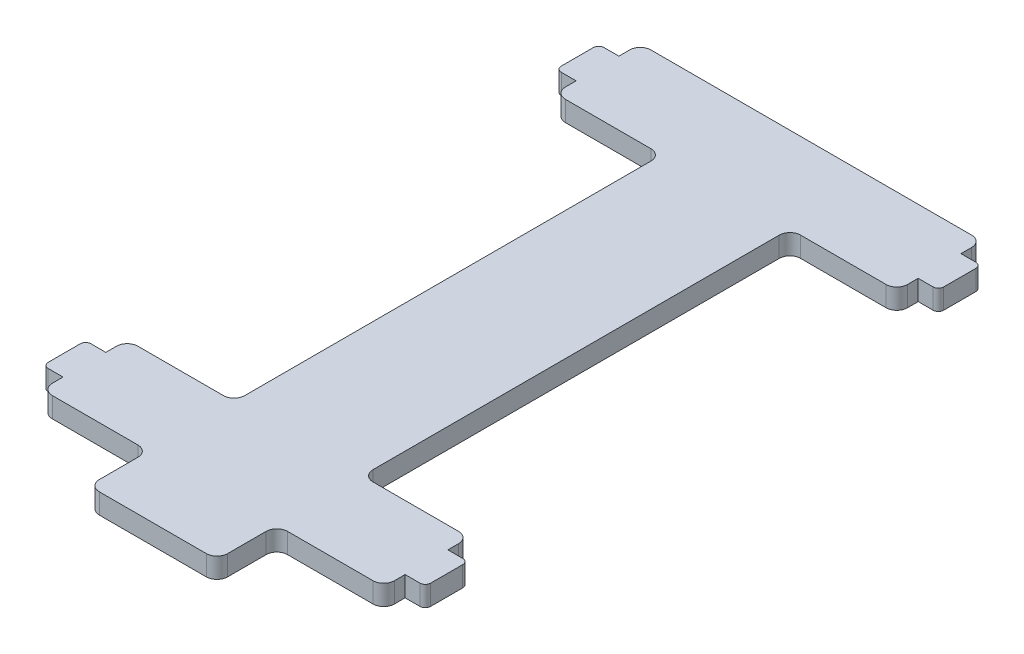
SolidWorks part; units mm, degrees
ref_plane "Front Plane" through (0, 0, 0) normal (0, 0, 1) x (1, 0, 0)
ref_plane "Top Plane" through (0, 0, 0) normal (0, 1, 0) x (1, 0, 0)
ref_plane "Right Plane" through (0, 0, 0) normal (1, 0, 0) x (0, 0, -1)
sketch "Sketch1" plane through (0, 0, 0) normal (0, 1, 0) x (1, 0, 0)
  line L0 (25.4, 31.75) -> (9.525, 31.75)
  line L1 (-25.4, -44.45) -> (-9.525, -44.45)
  line L2 (-25.4, -44.45) -> (-25.4, -31.75)
  line L4 (25.4, -44.45) -> (25.4, -31.75)
  line L5 (-25.4, -44.45) -> (25.4, 44.45) construction
  line L6 (-25.4, 44.45) -> (25.4, -44.45) construction
  line L7 (9.525, 31.75) -> (9.525, -31.75)
  line L8 (9.525, -31.75) -> (25.4, -31.75)
  line L9 (-25.4, -31.75) -> (-9.525, -31.75)
  line L10 (-9.525, -31.75) -> (-9.525, 31.75)
  line L11 (-9.525, 31.75) -> (-25.4, 31.75)
  line L12 (0, -44.45) -> (0, 44.45) construction
  line L13 (-25.4, -31.75) -> (-25.4, 31.75) construction
  line L14 (-25.4, 31.75) -> (-25.4, 44.45)
  line L15 (25.4, -31.75) -> (25.4, 31.75) construction
  line L16 (25.4, 31.75) -> (25.4, 44.45)
  line L20 (0, -44.45) -> (9.525, -44.45) construction
  line L21 (9.525, -44.45) -> (25.4, -44.45)
  line L22 (-9.525, -44.45) -> (0, -44.45) construction
  line L26 (-9.525, 44.45) -> (0, 44.45) construction
  line L27 (-25.4, 44.45) -> (25.4, 44.45)
  line L28 (0, 44.45) -> (-25.4, 44.45) construction
  line L29 (-9.525, -44.45) -> (-9.525, -53.34)
  line L30 (-9.525, -53.34) -> (9.525, -53.34)
  line L31 (9.525, -53.34) -> (9.525, -44.45)
  point P0 (0, 0)
  point P16 (10.5026, -44.45)
  point P18 (5.8448, -44.45)
  point P24 (-11.3356, -44.45)
  dimension "D1" = 50.8
  dimension "D2" = 88.9
  dimension "D3" = 12.7
  dimension "D4" = 12.7
  dimension "D5" = 19.05
  dimension "D6" = 8.89
  dimension "D7" = 19.05
extrude "Boss-Extrude1" add sketch "Sketch1" along normal mid plane 3
fillet "Fillet1" radius 1.5875 16 edges at (25.4, 0, -31.75) (9.525, 0, -31.75) (9.525, 0, 31.75) (25.4, 0, 31.75) (-25.4, 0, 31.75) (-9.525, 0, 31.75) (-9.525, 0, -31.75) (-25.4, 0, -31.75) (-25.4, 0, 44.45) (25.4, 0, 44.45) (25.4, 0, -44.45) (9.525, 0, 44.45) (9.525, 0, 53.34) (-9.525, 0, 44.45) (-25.4, 0, -44.45) (-9.525, 0, 53.34)
sketch "Sketch2" plane through (0, 1.5, 0) normal (0, 1, 0) x (1, 0, 0)
  line L5 (-25.4, 31.75) -> (-25.4, 44.45) construction
  line L6 (-26.9, 38.1) -> (-25.4, 38.1) construction
  line L12 (-25.4, -44.45) -> (-25.4, -31.75) construction
  line L13 (25.4, 31.75) -> (25.4, 44.45) construction
  line L14 (25.4, -44.45) -> (25.4, -31.75) construction
  line L15 (-26.9, -38.1) -> (-25.4, -38.1) construction
  line B0 (-28.4, 34.925) -> (-25.4, 34.925)
  line B1 (-28.4, 34.925) -> (-28.4, 41.275)
  line B2 (-28.4, 41.275) -> (-25.4, 41.275)
  line B3 (-25.4, 34.925) -> (-25.4, 41.275)
  line B4 (-28.4, 34.925) -> (-25.4, 41.275) construction
  line B5 (-28.4, 41.275) -> (-25.4, 34.925) construction
  line B6 (25.4, 34.925) -> (28.4, 34.925)
  line B7 (25.4, 34.925) -> (25.4, 41.275)
  line B8 (25.4, 41.275) -> (28.4, 41.275)
  line B9 (28.4, 34.925) -> (28.4, 41.275)
  line B10 (25.4, -41.275) -> (28.4, -41.275)
  line B11 (25.4, -41.275) -> (25.4, -34.925)
  line B12 (25.4, -34.925) -> (28.4, -34.925)
  line B13 (28.4, -41.275) -> (28.4, -34.925)
  line B14 (-28.4, -41.275) -> (-25.4, -41.275)
  line B15 (-28.4, -41.275) -> (-28.4, -34.925)
  line B16 (-28.4, -34.925) -> (-25.4, -34.925)
  line B17 (-25.4, -41.275) -> (-25.4, -34.925)
sketch_block_instance "Block1-1"
sketch_block "Block1" parameters "D1"=6.35, "D2"=3
sketch_block_instance "Block1-2"
sketch_block_instance "Block1-3"
sketch_block_instance "Block1-4"
extrude "Boss-Extrude2" add sketch "Sketch2" against normal up to surface (3 mm away) up to face at (0, -1.5, 12.2238)
fillet "Fillet2" radius 0.7937 8 edges at (-28.4, 0, 41.275) (-28.4, 0, 34.925) (28.4, 0, 34.925) (28.4, 0, 41.275) (28.4, 0, -41.275) (28.4, 0, -34.925) (-28.4, 0, -41.275) (-28.4, 0, -34.925)
